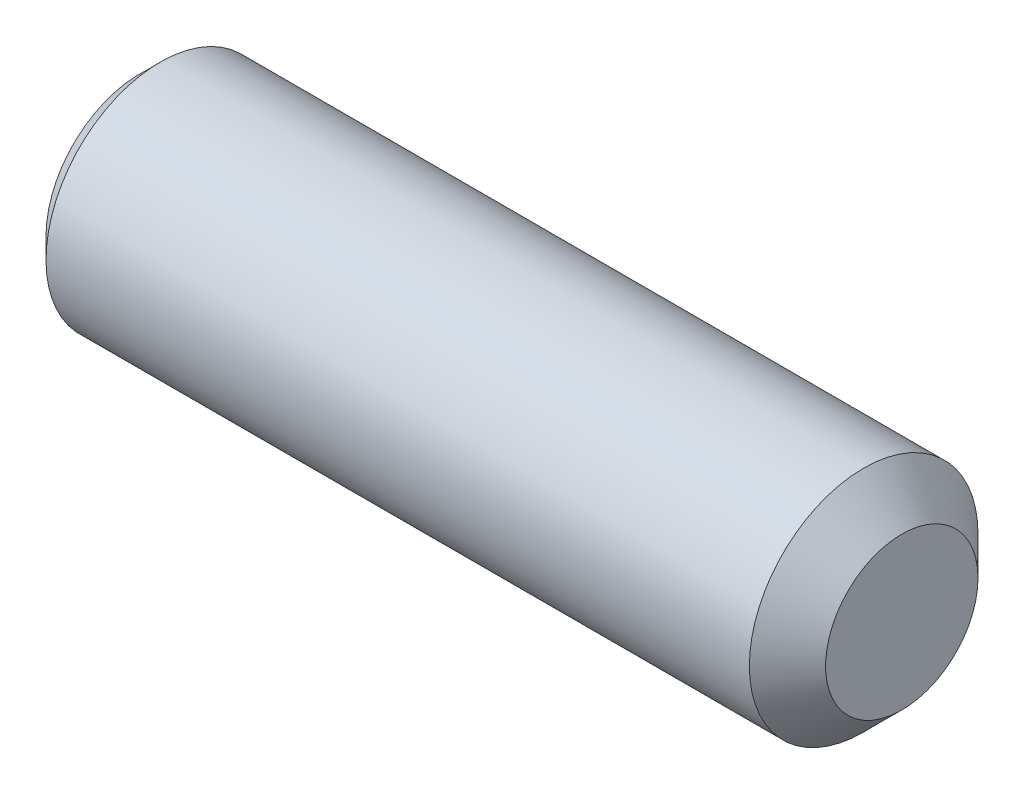
SolidWorks part; units mm, degrees
material "Plain Carbon Steel"
ref_plane "Front Plane" through (0, 0, 0) normal (0, 0, 1) x (1, 0, 0)
ref_plane "Top Plane" through (0, 0, 0) normal (0, 1, 0) x (1, 0, 0)
ref_plane "Right Plane" through (0, 0, 0) normal (1, 0, 0) x (0, 0, -1)
ref_plane "Plane1" through (0, 0, 0) normal (0, 0, -1) x (-1, 0, 0)
sketch "Sketch1" plane through (0, 0, 0) normal (0, 0, -1) x (-1, 0, 0)
  line L0 (-10, 1.5) -> (-10, 0)
  line L1 (-10, 0) -> (0, 0)
  line L2 (0, 0) -> (0, 1.5)
  line L3 (0, 1.5) -> (-10, 1.5)
  line L4 (-10, 0) -> (0, 0) construction
revolve "Revolve1" add sketch "Sketch1" angle 360 about L4
cosmetic thread "Cosmetic Thread1" parameters "D1"=5, "D2"=2.439
sketch "Sketch2" plane through (0, 0, 0) normal (-1, 0, 0) x (0, 0, 1)
  line L0 (-0.75, -0.433) -> (0, -0.866)
  line L1 (0, -0.866) -> (0.75, -0.433)
  line L2 (0.75, -0.433) -> (0.75, 0.433)
  line L3 (0.75, 0.433) -> (0, 0.866)
  line L4 (0, 0.866) -> (-0.75, 0.433)
  line L5 (-0.75, 0.433) -> (-0.75, -0.433)
extrude "Cut-Extrude1" cut sketch "Sketch2" against normal blind 1.2
chamfer "Chamfer1" distance 0.2706 angle 45 1 edges at (0, 0, 1.5)
chamfer "Chamfer2" distance 0.5 angle 45 1 edges at (10, 0, 1.5)
